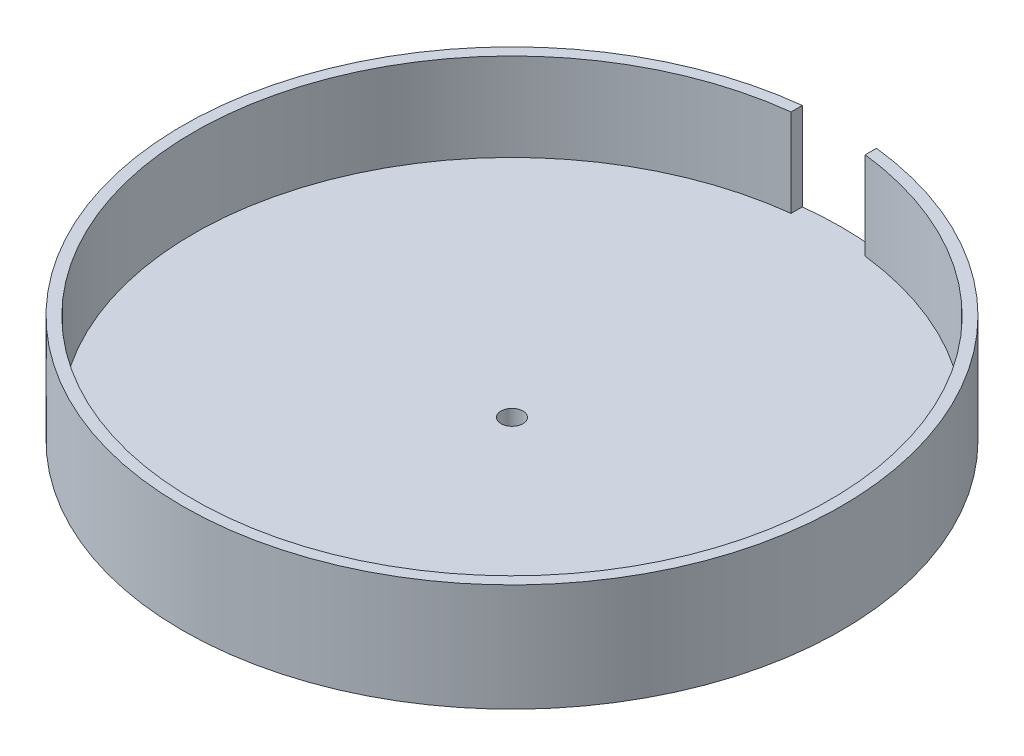
SolidWorks part; units mm, degrees
ref_plane "Front Plane" through (0, 0, 0) normal (0, 0, 1) x (1, 0, 0)
ref_plane "Top Plane" through (0, 0, 0) normal (0, 1, 0) x (1, 0, 0)
ref_plane "Right Plane" through (0, 0, 0) normal (1, 0, 0) x (0, 0, -1)
sketch "Sketch2" plane through (0, 0, 0) normal (0, 1, 0) x (1, 0, 0)
  circle A0 centre (0, 0) radius 150
  circle A1 centre (0, 0) radius 5
extrude "Boss-Extrude1" add sketch "Sketch2" along normal blind 9
sketch "Sketch3" plane through (0, 9, 0) normal (0, 1, 0) x (1, 0, 0)
  circle A1 centre (0, 0) radius 147.0359
  circle M1 centre (0, 0) radius 150
sketch "Sketch4" plane through (0, 9, 0) normal (0, 1, 0) x (1, 0, 0)
extrude "Boss-Extrude2" add sketch "Sketch3" along normal blind 40 contours A1 M1
sketch "Sketch9" plane through (0, 49, 0) normal (0, 1, 0) x (1, 0, 0)
  circle A0 centre (0, 0) radius 144.907
extrude "Cut-Extrude2" cut sketch "Sketch9" against normal blind 40
sketch "Sketch10" plane through (0, 9, 0) normal (0, 1, 0) x (1, 0, 0)
  circle A0 centre (0, 0) radius 5
  point P3 (0, 0)
sketch "Sketch11" plane through (0, 49, 0) normal (0, 1, 0) x (1, 0, 0)
  line L1 (-16.8871, 156.0804) -> (16.8871, 156.0804)
  line L2 (-16.8871, 156.0804) -> (-16.8871, 143.9196)
  line L3 (-16.8871, 143.9196) -> (16.8871, 143.9196)
  line L4 (16.8871, 156.0804) -> (16.8871, 143.9196)
  line L5 (-16.8871, 156.0804) -> (16.8871, 143.9196) construction
  line L6 (-16.8871, 143.9196) -> (16.8871, 156.0804) construction
  circle A0 centre (0, 0) radius 150 construction
  circle A1 centre (0, 0) radius 144.907 construction
  point P0 (0, 150)
extrude "Cut-Extrude9" cut sketch "Sketch11" against normal blind 40
